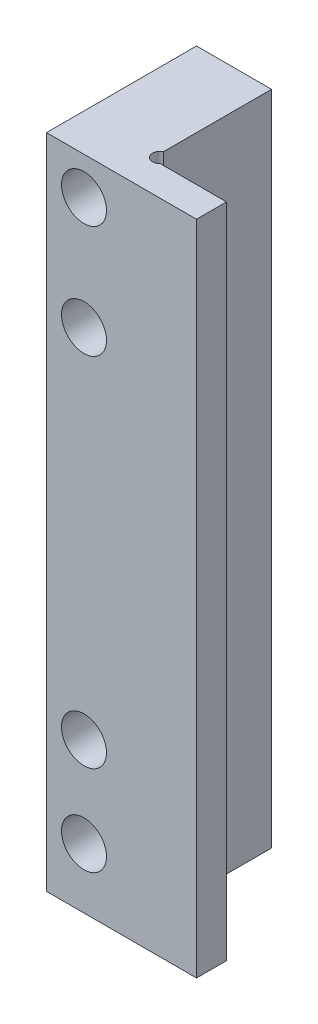
SolidWorks part; units mm, degrees
ref_plane "前基準面" through (0, 0, 0) normal (0, 0, 1) x (1, 0, 0)
ref_plane "上基準面" through (0, 0, 0) normal (0, 1, 0) x (1, 0, 0)
ref_plane "右基準面" through (0, 0, 0) normal (1, 0, 0) x (0, 0, -1)
sketch "草圖1" plane through (0, 0, 0) normal (0, 0, 1) x (1, 0, 0)
  line L0 (-29.9, 26.9) -> (-29.9, -26.9) construction
  line L1 (-38, 30) -> (38, 30) construction
  line L2 (-38, 30) -> (-38, -30) construction
  line L3 (-38, -30) -> (38, -30) construction
  line L4 (38, 30) -> (38, -30) construction
  line L5 (-38, 30) -> (38, -30) construction
  line L6 (-38, -30) -> (38, 30) construction
  line L7 (-29.9, 26.9) -> (29.9, 26.9) construction
  line L8 (-34.9, 21.9) -> (-34.9, -21.9) construction
  line L9 (-29.9, -26.9) -> (29.9, -26.9) construction
  line L10 (34.9, 21.9) -> (34.9, -21.9) construction
  line L11 (-34.9, 26.9) -> (34.9, -26.9) construction
  line L12 (-34.9, -26.9) -> (34.9, 26.9) construction
  line L13 (-34.9, 21.9) -> (-24.9, 21.9)
  line L14 (-24.9, 21.9) -> (-24.9, -21.9)
  line L15 (-24.9, -21.9) -> (-34.9, -21.9)
  line L16 (-34.9, 21.9) -> (-34.9, -21.9)
  arc A0 (29.9, -26.9) -> (34.9, -21.9) centre (29.9, -21.9) ccw construction
  arc A1 (29.9, 26.9) -> (34.9, 21.9) centre (29.9, 21.9) cw construction
  arc A2 (-34.9, -21.9) -> (-29.9, -26.9) centre (-29.9, -21.9) ccw construction
  arc A3 (-29.9, 26.9) -> (-34.9, 21.9) centre (-29.9, 21.9) ccw construction
  point P0 (0, 0)
  point P6 (0, 0)
  dimension "D5" = 5
  dimension "D1" = 76
  dimension "D2" = 60
  dimension "D3" = 3.1
  dimension "D4" = 3.1
  dimension "D6" = 5
  dimension "D7" = 10
extrude "填料-伸長1" add sketch "草圖1" against normal blind 10
sketch "草圖2" plane through (0, -21.9, 0) normal (0, -1, 0) x (1, 0, 0)
  line L0 (-24.9, -10) -> (-24.9, -2)
  line L1 (-24.9, -10) -> (-24.9, 0) construction
  line L2 (-24.9, -2) -> (-29.9, -2)
  line L3 (-29.9, -2) -> (-29.9, -10)
  line L4 (-34.9, -10) -> (-24.9, -10) construction
  line L5 (-29.9, -10) -> (-24.9, -10)
  line L6 (-27.4, -2) -> (-27.4, -10) construction
  line L7 (-29.9, -6) -> (-24.9, -6) construction
  line L8 (-27.4, -6) -> (-29.9, -2) construction
  circle A0 centre (-29.684, -2.3456) radius 0.5
  dimension "D3" = 1
  dimension "D4" = 0.3456
  dimension "D1" = 8
  dimension "D2" = 5
extrude "除料-伸長1" cut sketch "草圖2" against normal through all
sketch "草圖3" plane through (0, 0, 0) normal (0, 0, 1) x (1, 0, 0)
  line L0 (-34.9, -21.9) -> (-24.9, -21.9) construction
  line L1 (-34.9, 21.9) -> (-34.9, -21.9) construction
  line L2 (-24.9, 21.9) -> (-34.9, 21.9) construction
  circle A0 centre (-32.4, -17.9) radius 1.5
  circle A1 centre (-32.4, 19.4) radius 1.5
  dimension "D1" = 3
  dimension "D4" = 3
  dimension "D2" = 4
  dimension "D3" = 2.5
  dimension "D5" = 2.5
  dimension "D6" = 2.5
extrude "除料-伸長2" cut sketch "草圖3" against normal through all
sketch "草圖4" plane through (0, 0, 0) normal (0, 0, 1) x (1, 0, 0)
  line L0 (-34.9, 21.9) -> (-34.9, -21.9) construction
  line L1 (-24.9, 21.9) -> (-34.9, 21.9) construction
  line L2 (-34.9, 0) -> (-24.9, 0) construction
  line L3 (-24.9, -21.9) -> (-24.9, 21.9) construction
  circle A0 centre (-32.4, 11.9) radius 1.5
  circle A1 centre (-32.4, -11.9) radius 1.5
  dimension "D1" = 2.5
  dimension "D3" = 3
  dimension "D2" = 10
extrude "除料-伸長3" cut sketch "草圖4" against normal blind 5
